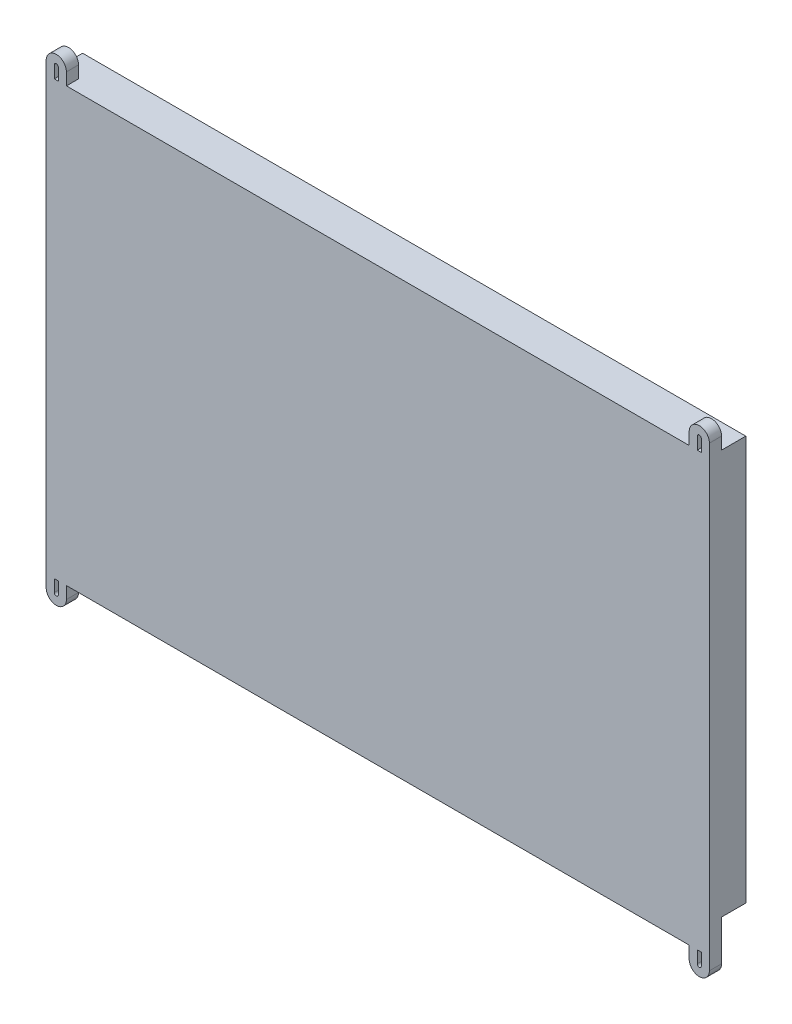
SolidWorks part; units mm, degrees
ref_plane "Plano frontal" through (0, 0, 0) normal (0, 0, 1) x (1, 0, 0)
ref_plane "Plano superior" through (0, 0, 0) normal (0, 1, 0) x (1, 0, 0)
ref_plane "Plano direito" through (0, 0, 0) normal (1, 0, 0) x (0, 0, -1)
ref_plane "Plano1" through (0, 0, -4.5) normal (0, 0, -1) x (-1, 0, 0)
sketch "Esboço1" plane through (0, 0, -4.5) normal (0, 0, -1) x (-1, 0, 0)
  line L0 (89.6416, 54.9017) -> (-74.3584, 54.9017)
  line L1 (-74.3584, 54.9017) -> (-74.3584, -45.0983)
  line L2 (-74.3584, -45.0983) -> (89.6416, -45.0983)
  line L3 (89.6416, -45.0983) -> (89.6416, 54.9017)
extrude "Ressalto-extrusão1" add sketch "Esboço1" against normal blind 6
sketch "Esboço2" plane through (0, 0, 1.5) normal (0, 0, 1) x (1, 0, 0)
  line L0 (71.3584, 54.9017) -> (72.3584, 54.9017)
  line L1 (72.3584, 54.9017) -> (72.3584, 57.9017)
  line L2 (71.3584, 57.9017) -> (71.3584, 54.9017)
  line L3 (-87.6416, 54.9017) -> (-86.6416, 54.9017)
  line L4 (-86.6416, 54.9017) -> (-86.6416, 57.9017)
  line L5 (-87.6416, 57.9017) -> (-87.6416, 54.9017)
  line L6 (-89.6416, -55.0983) -> (-89.6416, 57.9017)
  line L7 (-84.6416, 57.9017) -> (-84.6416, 54.9017)
  line L8 (-84.6416, 54.9017) -> (69.3584, 54.9017)
  line L9 (69.3584, 54.9017) -> (69.3584, 57.9017)
  line L10 (74.3584, 57.9017) -> (74.3584, -55.0983)
  line L11 (69.3584, -55.0983) -> (69.3584, -52.0983)
  line L12 (69.3584, -52.0983) -> (-84.6416, -52.0983)
  line L13 (-84.6416, -52.0983) -> (-84.6416, -55.0983)
  arc A0 (72.3584, 57.9017) -> (71.3584, 57.9017) centre (71.8584, 57.9017) ccw
  arc A1 (-86.6416, 57.9017) -> (-87.6416, 57.9017) centre (-87.1416, 57.9017) ccw
  arc A2 (-89.6416, 57.9017) -> (-84.6416, 57.9017) centre (-87.1416, 57.9017) cw
  arc A3 (69.3584, 57.9017) -> (74.3584, 57.9017) centre (71.8584, 57.9017) cw
  arc A4 (74.3584, -55.0983) -> (69.3584, -55.0983) centre (71.8584, -55.0983) cw
  arc A5 (-84.6416, -55.0983) -> (-89.6416, -55.0983) centre (-87.1416, -55.0983) cw
extrude "Ressalto-extrusão2" add sketch "Esboço2" along normal blind 3
sketch "Esboço3" plane through (0, 0, 1.5) normal (0, 0, -1) x (-1, 0, 0)
  line L0 (87.6416, -52.0983) -> (86.6416, -52.0983)
  line L1 (86.6416, -52.0983) -> (86.6416, -55.0983)
  line L2 (87.6416, -55.0983) -> (87.6416, -52.0983)
  arc A0 (86.6416, -55.0983) -> (87.6416, -55.0983) centre (87.1416, -55.0983) ccw
extrude "Corte-extrusão1" cut sketch "Esboço3" against normal through all
sketch "Esboço4" plane through (0, 0, 4.5) normal (0, 0, 1) x (1, 0, 0)
  line L0 (71.3584, -52.0983) -> (71.3584, -55.0983)
  line L1 (72.3584, -55.0983) -> (72.3584, -52.0983)
  line L2 (72.3584, -52.0983) -> (71.3584, -52.0983)
  arc A0 (71.3584, -55.0983) -> (72.3584, -55.0983) centre (71.8584, -55.0983) ccw
extrude "Corte-extrusão2" cut sketch "Esboço4" against normal through all
sketch "Esboço5" plane through (0, 0, -4.5) normal (0, 0, -1) x (-1, 0, 0)
  line L0 (-70.3584, -37.3244) -> (83.4321, -37.3244)
  line L1 (83.4321, -37.3244) -> (83.4321, 51.9017)
  line L2 (83.4321, 51.9017) -> (-70.3584, 51.9017)
  line L3 (-70.3584, 51.9017) -> (-70.3584, -37.3244)
extrude "Corte-extrusão3" cut sketch "Esboço5" against normal blind 1
